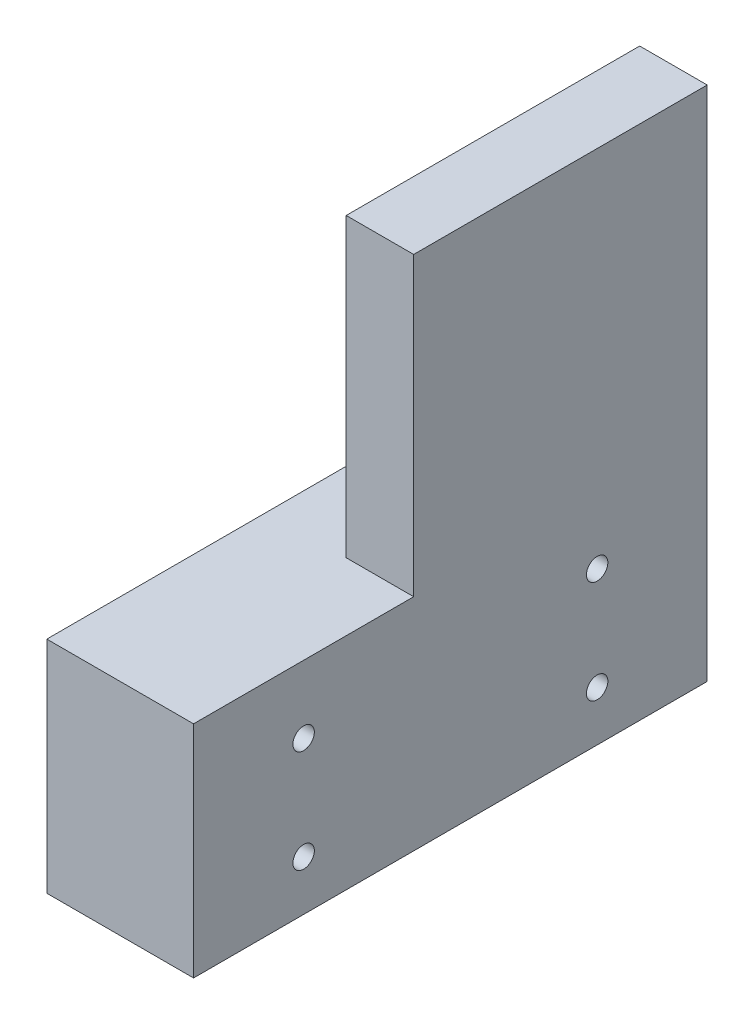
SolidWorks part; units mm, degrees
ref_plane "Front Plane" through (0, 0, 0) normal (0, 0, 1) x (1, 0, 0)
ref_plane "Top Plane" through (0, 0, 0) normal (0, 1, 0) x (1, 0, 0)
ref_plane "Right Plane" through (0, 0, 0) normal (1, 0, 0) x (0, 0, -1)
sketch "Sketch1" plane through (0, 0, 0) normal (1, 0, 0) x (0, 0, -1)
  line L1 (0, 0) -> (44.45, 0)
  line L2 (0, 0) -> (0, 19.05)
  line L3 (0, 19.05) -> (44.45, 19.05)
  line L4 (44.45, 0) -> (44.45, 19.05)
  point P6 (0, 0)
  dimension "D1" = 44.45
  dimension "D2" = 19.05
extrude "Boss-Extrude1" add sketch "Sketch1" along normal blind 12.7
sketch "Sketch3" plane through (0, 0, 0) normal (1, 0, 0) x (0, 0, -1)
  line L1 (44.45, 19.05) -> (0, 19.05) construction
  line L2 (0, 19.05) -> (0, 0) construction
  circle A0 centre (9.525, 4.318) radius 0.927
  circle A1 centre (34.925, 4.318) radius 0.927
  circle A2 centre (34.925, 13.208) radius 0.927
  circle A3 centre (9.525, 13.208) radius 0.927
  dimension "D1" = 1.854
  dimension "D2" = 5.842
  dimension "D5" = 9.525
  dimension "D3" = 2
  dimension "D4" = 2
extrude "Cut-Extrude1" cut sketch "Sketch3" along normal through all
sketch "Sketch4" plane through (0, 19.05, 0) normal (0, 1, 0) x (1, 0, 0)
  line L1 (12.7, 44.45) -> (6.858, 44.45)
  line L2 (12.7, 44.45) -> (12.7, 19.05)
  line L3 (12.7, 19.05) -> (6.858, 19.05)
  line L4 (6.858, 44.45) -> (6.858, 19.05)
  dimension "D1" = 5.842
  dimension "D2" = 25.4
extrude "Boss-Extrude2" add sketch "Sketch4" along normal blind 25.654
equation "\"tightTol\" = 0.005in"
equation "\"normTol\"= 0.01in"
equation "\"looseTol\"= 0.02in"
equation "\"D1@Sketch3\"=\"normTol\"+1.6mm"
equation "\"D2@Sketch3\"=0.25-\"looseTol\""
equation "\"D1@Sketch4\"=0.25-\"looseTol\""
equation "\"D1@Boss-Extrude2\"=1.000000in+\"normTol\""
